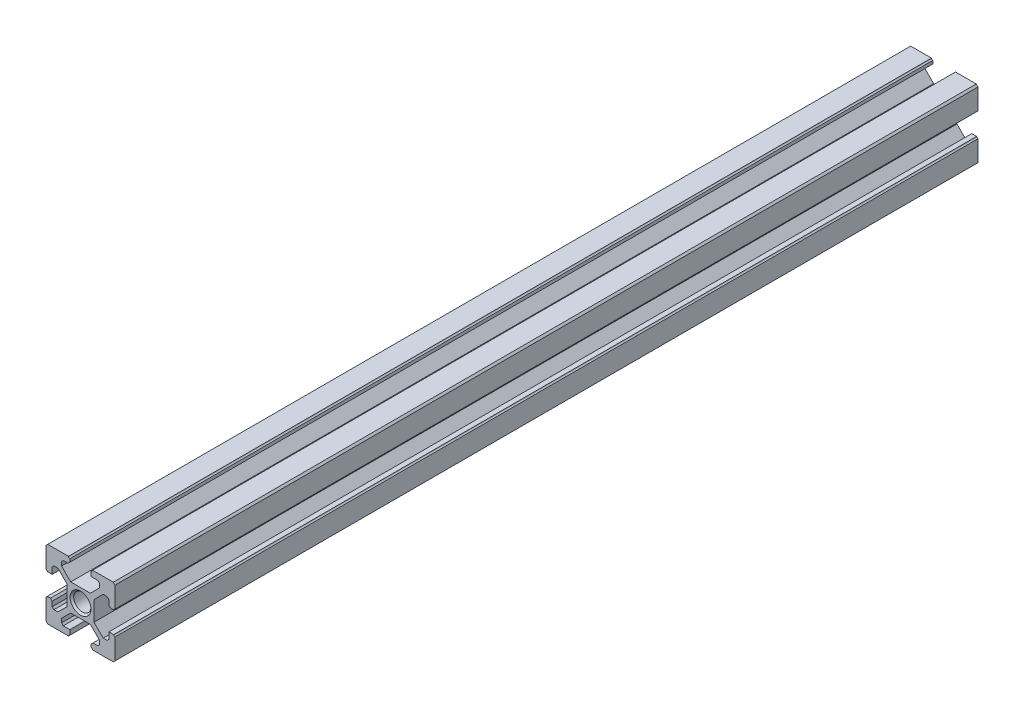
SolidWorks part; units mm, degrees
ref_plane "Front Plane" through (0, 0, 0) normal (0, 0, 1) x (1, 0, 0)
ref_plane "Top Plane" through (0, 0, 0) normal (0, 1, 0) x (1, 0, 0)
ref_plane "Right Plane" through (0, 0, 0) normal (1, 0, 0) x (0, 0, -1)
sketch "Sketch1" plane through (0, 0, 0) normal (0, 0, 1) x (1, 0, 0)
  line L0 (0, 10.7337) -> (0, 0.7337) construction
  line L1 (-9.5, 10) -> (-3.4865, 10)
  line L2 (-10, 9.5) -> (-10, 3.4865)
  line L3 (-9.5, -10) -> (-3.4865, -10)
  line L4 (10, 9.5) -> (10, 3.4865)
  line L5 (-9.75, 9.75) -> (9.75, -9.75) construction
  line L6 (-9.75, -9.75) -> (10, 10) construction
  line L7 (0, 0) -> (-10, 0) construction
  line L8 (3.1, 9.6135) -> (3.1, 8.2)
  line L9 (3.1, 8.2) -> (5, 8.2)
  line L10 (5.5, 7.7) -> (5.5, 6.5607)
  line L11 (5.5, 6.5607) -> (2.8393, 3.9)
  line L12 (2.8393, 3.9) -> (0, 3.9)
  line L13 (3.9, 2.8393) -> (3.9, 0)
  line L14 (6.5607, 5.5) -> (3.9, 2.8393)
  line L15 (9.6135, 3.1) -> (8.7, 3.1)
  line L16 (8.2, 3.6) -> (8.2, 5)
  line L17 (7.7, 5.5) -> (6.5607, 5.5)
  line L18 (3.4865, 10) -> (9.5, 10)
  line L19 (10, -3.4865) -> (10, -9.5)
  line L20 (5, 8.2) -> (5.5, 7.7)
  line L21 (8.2, 5) -> (7.7, 5.5)
  line L22 (9.5, 10) -> (10, 9.5)
  line L23 (8.7, 3.1) -> (8.2, 3.6)
  line L24 (3.9, -2.8393) -> (3.9, 0)
  line L25 (6.5607, -5.5) -> (3.9, -2.8393)
  line L26 (7.7, -5.5) -> (6.5607, -5.5)
  line L27 (8.2, -5) -> (7.7, -5.5)
  line L28 (8.2, -3.1) -> (8.2, -5)
  line L29 (9.6135, -3.1) -> (8.2, -3.1)
  line L30 (10, -3.4865) -> (10, -9.5)
  line L31 (10, -9.5) -> (9.5, -10)
  line L32 (9.5, -10) -> (3.4865, -10)
  line L33 (3.1, -9.6135) -> (3.1, -8.7)
  line L34 (3.1, -8.7) -> (3.6, -8.2)
  line L35 (3.6, -8.2) -> (5, -8.2)
  line L36 (5, -8.2) -> (5.5, -7.7)
  line L37 (5.5, -7.7) -> (5.5, -6.5607)
  line L38 (5.5, -6.5607) -> (2.8393, -3.9)
  line L39 (2.8393, -3.9) -> (0, -3.9)
  line L40 (-2.8393, -3.9) -> (0, -3.9)
  line L41 (-5.5, -6.5607) -> (-2.8393, -3.9)
  line L42 (-5.5, -7.7) -> (-5.5, -6.5607)
  line L43 (-5, -8.2) -> (-5.5, -7.7)
  line L44 (-3.1, -8.2) -> (-5, -8.2)
  line L45 (-3.1, -9.6135) -> (-3.1, -8.2)
  line L46 (-3.4865, -10) -> (-9.5, -10)
  line L47 (-9.5, -10) -> (-10, -9.5)
  line L48 (-10, -9.5) -> (-10, -3.4865)
  line L49 (-9.6135, -3.1) -> (-8.7, -3.1)
  line L50 (-8.7, -3.1) -> (-8.2, -3.6)
  line L51 (-8.2, -3.6) -> (-8.2, -5)
  line L52 (-8.2, -5) -> (-7.7, -5.5)
  line L53 (-7.7, -5.5) -> (-6.5607, -5.5)
  line L54 (-6.5607, -5.5) -> (-3.9, -2.8393)
  line L55 (-3.9, -2.8393) -> (-3.9, 0)
  line L56 (-3.9, 2.8393) -> (-3.9, 0)
  line L57 (-6.5607, 5.5) -> (-3.9, 2.8393)
  line L58 (-7.7, 5.5) -> (-6.5607, 5.5)
  line L59 (-8.2, 5) -> (-7.7, 5.5)
  line L60 (-8.2, 3.1) -> (-8.2, 5)
  line L61 (-9.6135, 3.1) -> (-8.2, 3.1)
  line L62 (-10, 3.4865) -> (-10, 9.5)
  line L63 (-10, 9.5) -> (-9.5, 10)
  line L64 (-9.5, 10) -> (-3.4865, 10)
  line L65 (-3.1, 9.6135) -> (-3.1, 8.7)
  line L66 (-3.1, 8.7) -> (-3.6, 8.2)
  line L67 (-3.6, 8.2) -> (-5, 8.2)
  line L68 (-5, 8.2) -> (-5.5, 7.7)
  line L69 (-5.5, 7.7) -> (-5.5, 6.5607)
  line L70 (-5.5, 6.5607) -> (-2.8393, 3.9)
  line L71 (-2.8393, 3.9) -> (0, 3.9)
  line L72 (3.4865, -10) -> (9.5, -10)
  line L73 (-10, -3.4865) -> (-10, -9.5)
  arc A0 (3.1, 9.6135) -> (3.4865, 10) centre (3.1, 10) ccw
  arc A1 (9.6135, 3.1) -> (10, 3.4865) centre (10, 3.1) cw
  arc A2 (9.6135, -3.1) -> (10, -3.4865) centre (10, -3.1) ccw
  arc A3 (3.1, -9.6135) -> (3.4865, -10) centre (3.1, -10) cw
  arc A4 (-3.1, -9.6135) -> (-3.4865, -10) centre (-3.1, -10) ccw
  arc A5 (-9.6135, -3.1) -> (-10, -3.4865) centre (-10, -3.1) cw
  arc A6 (-9.6135, 3.1) -> (-10, 3.4865) centre (-10, 3.1) ccw
  arc A7 (-3.1, 9.6135) -> (-3.4865, 10) centre (-3.1, 10) cw
  point P0 (0, 0)
  point P13 (5.5, 8.2)
  point P17 (3.1, 8.9068)
  point P22 (8.2, 3.1)
  point P23 (8.2, 5.5)
  point P103 (0, 0)
  dimension "D3" = 1.8
  dimension "D4" = 6.1
  dimension "D5" = 11
  dimension "D6" = 6.2
  dimension "D7" = 1.5
extrude "Boss-Extrude1" add sketch "Sketch1" along normal blind 250 contours L65 A7 L1 L63 L2 A6 L61 L60 L59 L58 L57 L56 L55 L54 L53 L52 L51 L50 L49 A5 L48 L47 L3 A4 L45 L44 L43 L42 L41 L40 L39 L38 L37 L36 L35 L34 L33 A3 L32 L31 L19 A2 L29 L28 L27 L26 L25 L24 L13 L14 L17
hole_wizard "M6x1.0 Tapped Hole1" positions "3DSketch1" profile "Sketch2" tap size "M6x1.0" standard "ANSI Metric"
sketch3d "3DSketch1"
  line L0 (3.9, -2.8393, 250) -> (3.9, 2.8393, 250) construction
  line L1 (2.8393, 3.9, 250) -> (-2.8393, 3.9, 250) construction
  point P0 (0, 0, 0)
  point P3 (0, 0, 0)
  point P5 (0, 0, 0)
  point P7 (0.9996, -8.1302, 0)
  point P9 (0, 0, 0)
  point P11 (0, 0, 250)
  dimension "D1" = 3.9
  dimension "D2" = 3.9
sketch "Sketch2" plane through (0, 0, 250) normal (1, 0, 0) x (0, -1, 0)
  line L0 (0, 0) -> (0, 30)
  line L1 (0, 30) -> (2.5, 28.4978)
  line L2 (2.5, 28.4978) -> (2.5, 0.525)
  line L3 (2.5, 0.525) -> (3.025, 0)
  line L5 (3.025, 0) -> (0, 0)
  line L6 (-2.5, 0.525) -> (-3.025, 0) construction
  line L10 (0, 30) -> (-2.5, 28.4978) construction
  line L11 (0, -6.35) -> (0, 107.95) construction
  dimension "Tap Drill Dia." = 5
  dimension "Tap Drill Depth" = 30
  dimension "Near C'Sink Dia." = 6.05
  dimension "Near C'Sink Angle" = 90
  dimension "Drill Angle" = 118
cosmetic thread "Hole Thread6" parameters "D1"=12, "D2"=6
hole_wizard "M6x1.0 Tapped Hole2" positions "3DSketch2" profile "Sketch3" tap size "M6x1.0" standard "ANSI Metric"
sketch3d "3DSketch2"
  line L0 (2.8393, 3.9, 0) -> (-2.8393, 3.9, 0) construction
  line L1 (3.9, -2.8393, 0) -> (3.9, 2.8393, 0) construction
  point P3 (0, 0, 0)
  dimension "D1" = 3.9
  dimension "D2" = 3.9
sketch "Sketch3" plane through (0, 0, 0) normal (1, 0, 0) x (0, 1, 0)
  line L0 (0, 0) -> (0, 30)
  line L1 (0, 30) -> (2.5, 28.4978)
  line L2 (2.5, 28.4978) -> (2.5, 0.525)
  line L3 (2.5, 0.525) -> (3.025, 0)
  line L5 (3.025, 0) -> (0, 0)
  line L6 (-2.5, 0.525) -> (-3.025, 0) construction
  line L10 (0, 30) -> (-2.5, 28.4978) construction
  line L11 (0, -6.35) -> (0, 107.95) construction
  dimension "Tap Drill Dia." = 5
  dimension "Tap Drill Depth" = 30
  dimension "Near C'Sink Dia." = 6.05
  dimension "Near C'Sink Angle" = 90
  dimension "Drill Angle" = 118
cosmetic thread "Hole Thread7" parameters "D1"=12, "D2"=6
